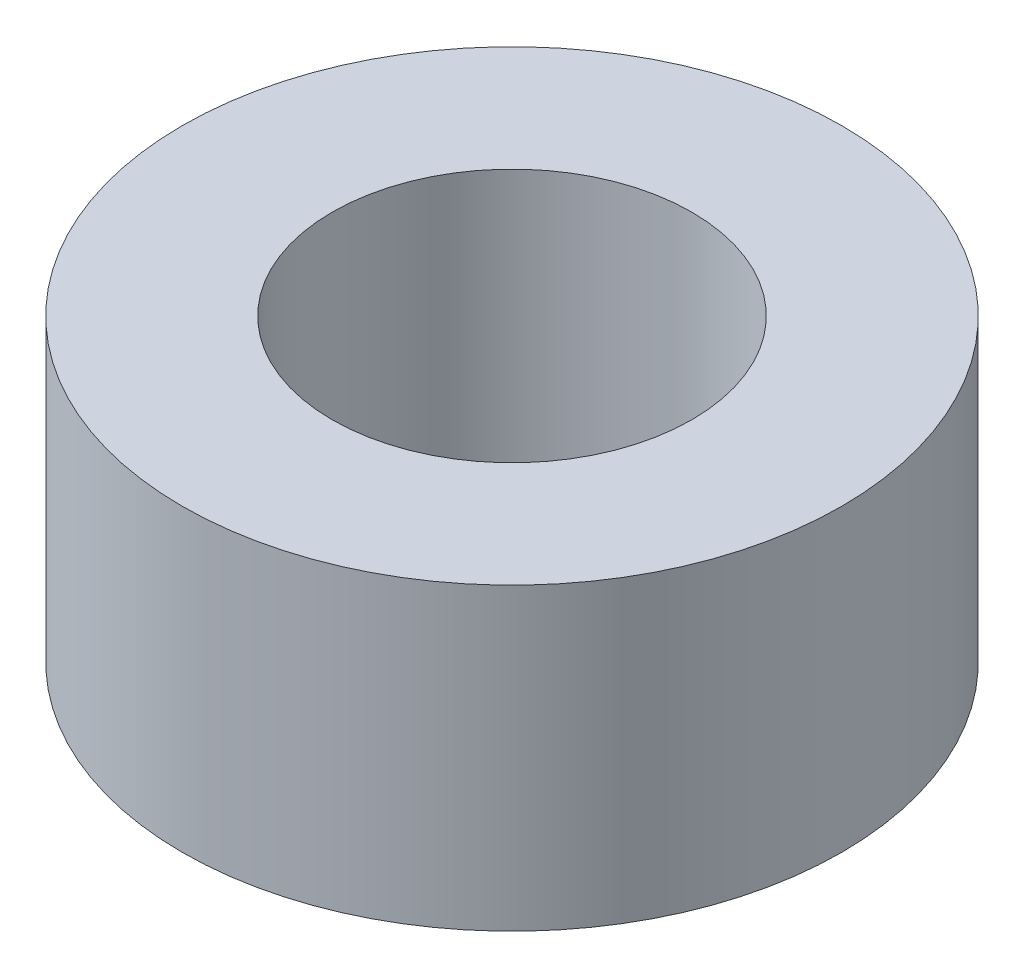
SolidWorks part; units mm, degrees
ref_plane "Front Plane" through (0, 0, 0) normal (0, 0, 1) x (1, 0, 0)
ref_plane "Top Plane" through (0, 0, 0) normal (0, 1, 0) x (1, 0, 0)
ref_plane "Right Plane" through (0, 0, 0) normal (1, 0, 0) x (0, 0, -1)
sketch "Sketch1" plane through (0, 0, 0) normal (0, 1, 0) x (1, 0, 0)
  circle A0 centre (0, 0) radius 1.8
  circle A1 centre (0, 0) radius 3.3
  dimension "D1" = 3.6
  dimension "D2" = 1.5
extrude "Boss-Extrude1" add sketch "Sketch1" along normal blind 3
